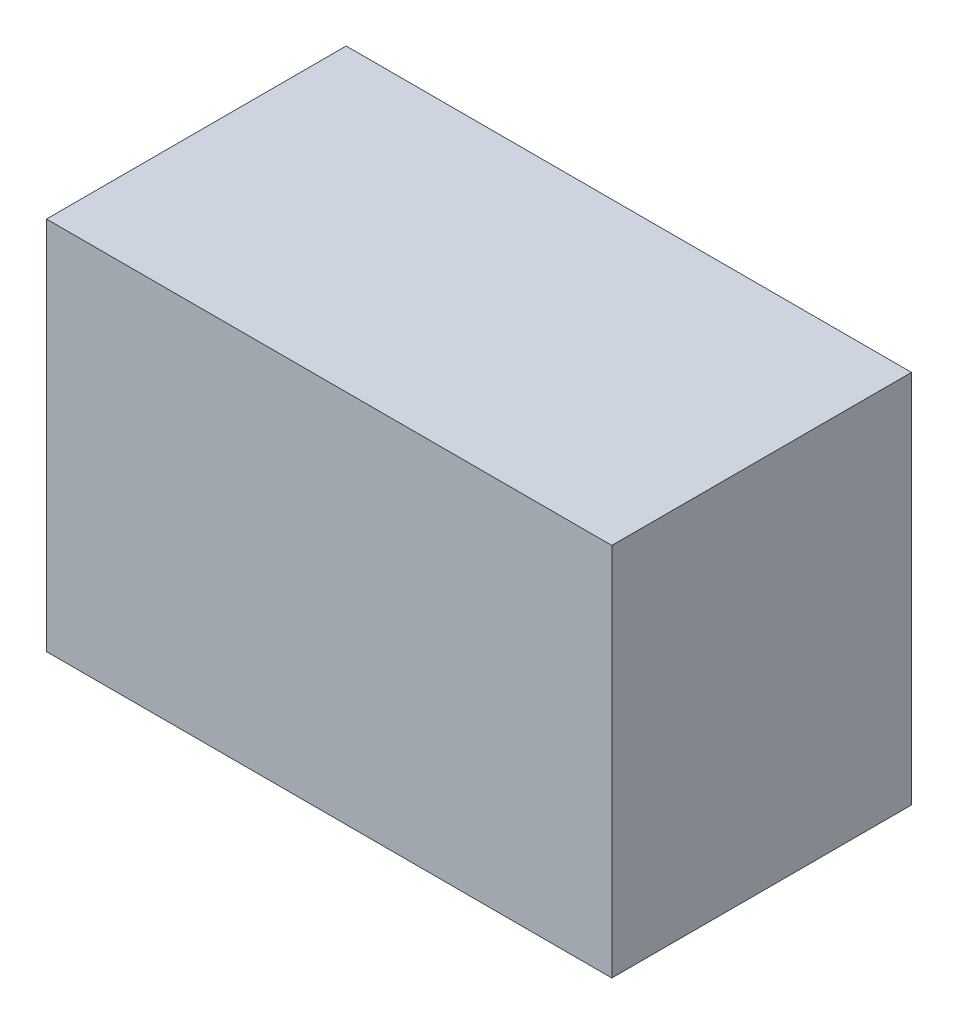
SolidWorks part; units mm, degrees
ref_plane "Front Plane" through (0, 0, 0) normal (0, 0, 1) x (1, 0, 0)
ref_plane "Top Plane" through (0, 0, 0) normal (0, 1, 0) x (1, 0, 0)
ref_plane "Right Plane" through (0, 0, 0) normal (1, 0, 0) x (0, 0, -1)
sketch "Sketch1" plane through (0, 0, 0) normal (0, 1, 0) x (1, 0, 0)
  line L1 (-166, 88) -> (166, 88)
  line L2 (-166, 88) -> (-166, -88)
  line L3 (-166, -88) -> (166, -88)
  line L4 (166, 88) -> (166, -88)
  line L5 (-166, 88) -> (166, -88) construction
  line L6 (-166, -88) -> (166, 88) construction
  point P0 (0, 0)
  dimension "Width" = 176
  dimension "Length" = 332
extrude "Boss-Extrude1" add sketch "Sketch1" along normal blind 220
